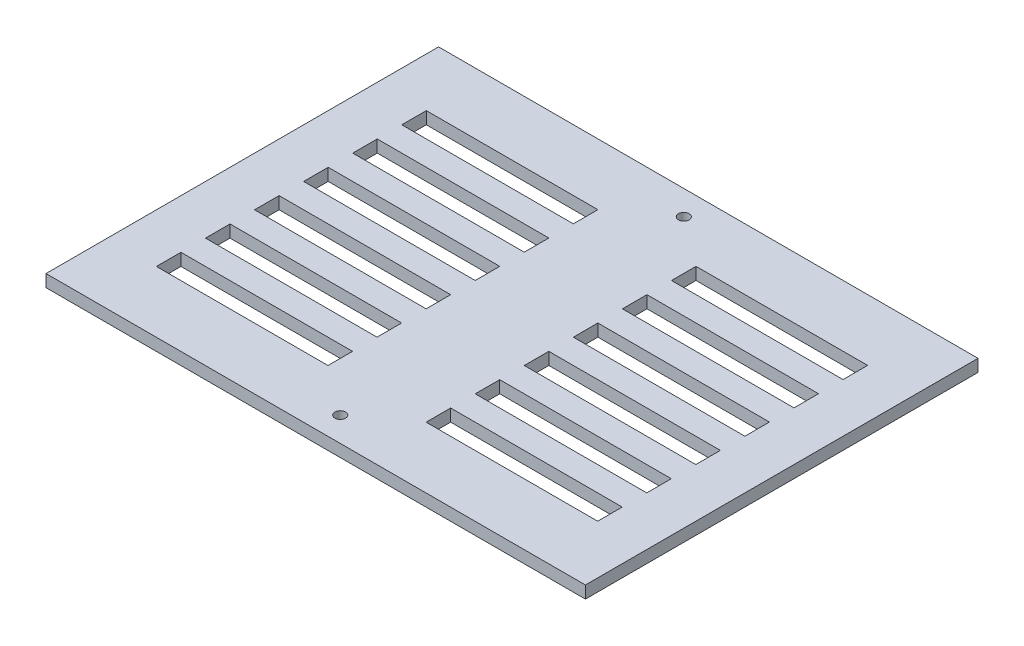
SolidWorks part; units mm, degrees
material "Birch Ply"
ref_plane "Front Plane" through (0, 0, 0) normal (0, 0, 1) x (1, 0, 0)
ref_plane "Top Plane" through (0, 0, 0) normal (0, 1, 0) x (1, 0, 0)
ref_plane "Right Plane" through (0, 0, 0) normal (1, 0, 0) x (0, 0, -1)
sketch "Sketch1" plane through (0, 0, 0) normal (0, 1, 0) x (1, 0, 0)
  line L0 (-55, 0) -> (55, 0) construction
  line L1 (-69.7992, 101.6) -> (69.7992, 101.6)
  line L2 (-69.7992, 101.6) -> (-69.7992, 0)
  line L3 (-69.7992, 0) -> (69.7992, 0)
  line L4 (69.7992, 101.6) -> (69.7992, 0)
  line L5 (0, 0) -> (0, 101.6) construction
  line L6 (0, -55) -> (0, 55) construction
  dimension "D1" = 101.6
  dimension "D2" = 139.5984
extrude "Boss-Extrude1" add sketch "Sketch1" along normal blind 3.175
sketch "Sketch2" plane through (0, 3.175, 0) normal (0, 1, 0) x (1, 0, 0)
  line L1 (-12.7, 101.6) -> (-12.7, 0) construction
  line L2 (-57.0992, 101.6) -> (-57.0992, 0) construction
  line L3 (-57.0992, 85.725) -> (-12.7, 85.725)
  line L4 (-57.0992, 85.725) -> (-57.0992, 79.375)
  line L5 (-57.0992, 79.375) -> (-12.7, 79.375)
  line L6 (-12.7, 85.725) -> (-12.7, 79.375)
  line L7 (-57.0992, 73.025) -> (-12.7, 73.025)
  line L8 (-57.0992, 73.025) -> (-57.0992, 66.675)
  line L9 (-69.7992, 101.6) -> (-69.7992, 0) construction
  line L10 (-57.0992, 66.675) -> (-12.7, 66.675)
  line L11 (57.0992, 101.6) -> (57.0992, -20.7809) construction
  line L12 (-12.7, 73.025) -> (-12.7, 66.675)
  line L13 (-57.0992, 60.325) -> (-12.7, 60.325)
  line L14 (-57.0992, 60.325) -> (-57.0992, 53.975)
  line L15 (-57.0992, 53.975) -> (-12.7, 53.975)
  line L16 (-12.7, 60.325) -> (-12.7, 53.975)
  line L17 (-57.0992, 47.625) -> (-12.7, 47.625)
  line L18 (-57.0992, 47.625) -> (-57.0992, 41.275)
  line L19 (-57.0992, 41.275) -> (-12.7, 41.275)
  line L20 (-12.7, 47.625) -> (-12.7, 41.275)
  line L21 (-57.0992, 34.925) -> (-12.7, 34.925)
  line L22 (-57.0992, 34.925) -> (-57.0992, 28.575)
  line L23 (-57.0992, 28.575) -> (-12.7, 28.575)
  line L24 (-12.7, 34.925) -> (-12.7, 28.575)
  line L25 (-57.0992, 22.225) -> (-12.7, 22.225)
  line L26 (-57.0992, 22.225) -> (-57.0992, 15.875)
  line L27 (-57.0992, 15.875) -> (-12.7, 15.875)
  line L28 (-12.7, 22.225) -> (-12.7, 15.875)
  line L29 (69.7992, 101.6) -> (-69.7992, 101.6) construction
  line L30 (-69.7992, 0) -> (69.7992, 0) construction
  line L31 (12.7, 101.6) -> (12.7, -20.7809) construction
  line L32 (12.7, 85.725) -> (57.0992, 85.725)
  line L33 (12.7, 85.725) -> (12.7, 79.375)
  line L34 (12.7, 79.375) -> (57.0992, 79.375)
  line L35 (57.0992, 85.725) -> (57.0992, 79.375)
  line L36 (12.7, 73.025) -> (57.0992, 73.025)
  line L37 (12.7, 73.025) -> (12.7, 66.675)
  line L38 (12.7, 66.675) -> (57.0992, 66.675)
  line L39 (57.0992, 73.025) -> (57.0992, 66.675)
  line L40 (12.7, 60.325) -> (57.0992, 60.325)
  line L41 (12.7, 60.325) -> (12.7, 53.975)
  line L42 (12.7, 53.975) -> (57.0992, 53.975)
  line L43 (57.0992, 60.325) -> (57.0992, 53.975)
  line L44 (12.7, 47.625) -> (57.0992, 47.625)
  line L45 (12.7, 47.625) -> (12.7, 41.275)
  line L46 (12.7, 41.275) -> (57.0992, 41.275)
  line L47 (57.0992, 47.625) -> (57.0992, 41.275)
  line L48 (12.7, 34.925) -> (57.0992, 34.925)
  line L49 (12.7, 34.925) -> (12.7, 28.575)
  line L50 (12.7, 28.575) -> (57.0992, 28.575)
  line L51 (57.0992, 34.925) -> (57.0992, 28.575)
  line L52 (12.7, 22.225) -> (57.0992, 22.225)
  line L53 (12.7, 22.225) -> (12.7, 15.875)
  line L54 (12.7, 15.875) -> (57.0992, 15.875)
  line L55 (57.0992, 22.225) -> (57.0992, 15.875)
  line L56 (69.7992, 0) -> (69.7992, 101.6) construction
  circle A0 centre (0, 6.35) radius 1.3843
  circle A1 centre (0, 95.25) radius 1.3843
  point P62 (69.7992, 50.8)
  dimension "D29" = 2.7686
  dimension "D30" = 2.7686
  dimension "D1" = 15.875
  dimension "D2" = 15.875
  dimension "D3" = 6.35
  dimension "D4" = 6.35
  dimension "D5" = 6.35
  dimension "D6" = 6.35
  dimension "D7" = 6.35
  dimension "D8" = 6.35
  dimension "D9" = 6.35
  dimension "D10" = 6.35
  dimension "D11" = 6.35
  dimension "D12" = 6.35
  dimension "D13" = 12.7
  dimension "D14" = 6.35
  dimension "D15" = 6.35
  dimension "D16" = 6.35
  dimension "D17" = 6.35
  dimension "D18" = 6.35
  dimension "D19" = 6.35
  dimension "D20" = 6.35
  dimension "D21" = 6.35
  dimension "D22" = 6.35
  dimension "D23" = 6.35
  dimension "D24" = 15.875
  dimension "D25" = 15.875
  dimension "D26" = 12.7
  dimension "D27" = 25.4
  dimension "D28" = 44.3992
  dimension "D31" = 6.35
  dimension "D32" = 6.35
extrude "Cut-Extrude1" cut sketch "Sketch2" against normal blind 3.175
